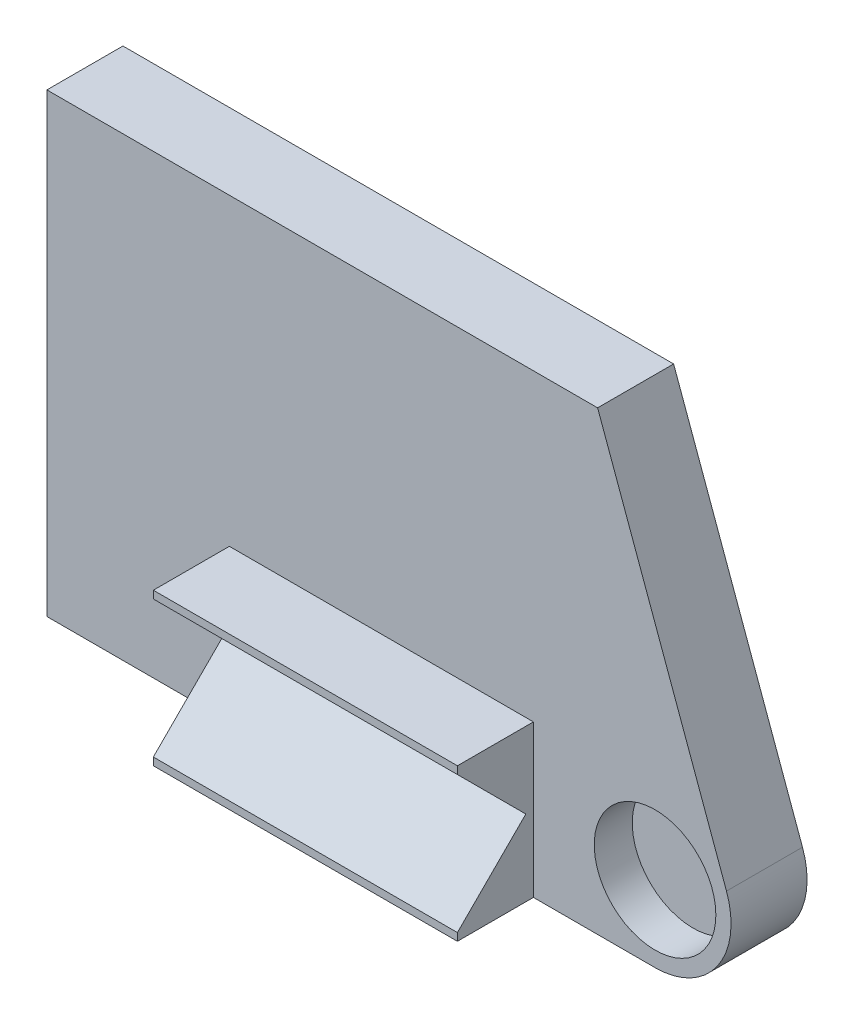
SolidWorks part; units mm, degrees
ref_plane "前视基准面" through (0, 0, 0) normal (0, 0, 1) x (1, 0, 0)
ref_plane "上视基准面" through (0, 0, 0) normal (0, 1, 0) x (1, 0, 0)
ref_plane "右视基准面" through (0, 0, 0) normal (1, 0, 0) x (0, 0, -1)
sketch "草图1" plane through (0, 0, 0) normal (0, 0, 1) x (1, 0, 0)
  line L0 (0, -5) -> (-40, -5)
  line L1 (-40, -5) -> (-40, 25)
  line L2 (-40, 25) -> (-3.7784, 25)
  line L3 (-3.7784, 25) -> (4.6985, 1.7101)
  circle A0 centre (0, 0) radius 5
  dimension "D1" = 10
  dimension "D2" = 70
  dimension "D3" = 40
  dimension "D4" = 30
extrude "凸台-拉伸1" add sketch "草图1" along normal blind 5 contours A0 | A0 L3 L2 L1 L0
sketch "草图2" plane through (0, 0, 5) normal (0, 0, 1) x (1, 0, 0)
  circle A0 centre (0, 0) radius 4
  dimension "D1" = 8
extrude "切除-拉伸1" cut sketch "草图2" against normal blind 2.5
sketch "草图3" plane through (0, 0, 5) normal (0, 0, 1) x (1, 0, 0)
  line L1 (-40, -5) -> (-8, -5)
  line L2 (-40, -5) -> (-40, 5)
  line L3 (-40, 5) -> (-8, 5)
  line L4 (-8, -5) -> (-8, 5)
  circle A0 centre (0, 0) radius 4 construction
  dimension "D2" = 8
  dimension "D1" = 10
extrude "凸台-拉伸2" add sketch "草图3" along normal blind 5
sketch "草图4" plane through (-8, 0, 0) normal (1, 0, 0) x (0, 0, -1)
  line L0 (-1010, 0) -> (48990, 0) construction
  line L1 (-10, -5) -> (-10, 5) construction
  line L2 (-10, 4.5) -> (-5.5, 0)
  line L3 (-5.5, 0) -> (-10, -4.5)
  line L4 (-10, -4.5) -> (-10, 4.5)
  point P5 (-10, 0)
  dimension "D1" = 9
  dimension "D2" = 45
extrude "切除-拉伸2" cut sketch "草图4" against normal blind 20
sketch "草图5" plane through (0, 0, 10) normal (0, 0, 1) x (1, 0, 0)
  line L0 (-40, -5) -> (-8, -5) construction
  line L1 (-28, -5) -> (-40, -5)
  line L2 (-28, -5) -> (-28, 5)
  line L3 (-28, 5) -> (-40, 5)
  line L4 (-40, -5) -> (-40, 5)
  line L5 (-28, -4.5) -> (-28, 0) construction
  point P7 (-28, -5)
extrude "切除-拉伸3" cut sketch "草图5" against normal blind 5
